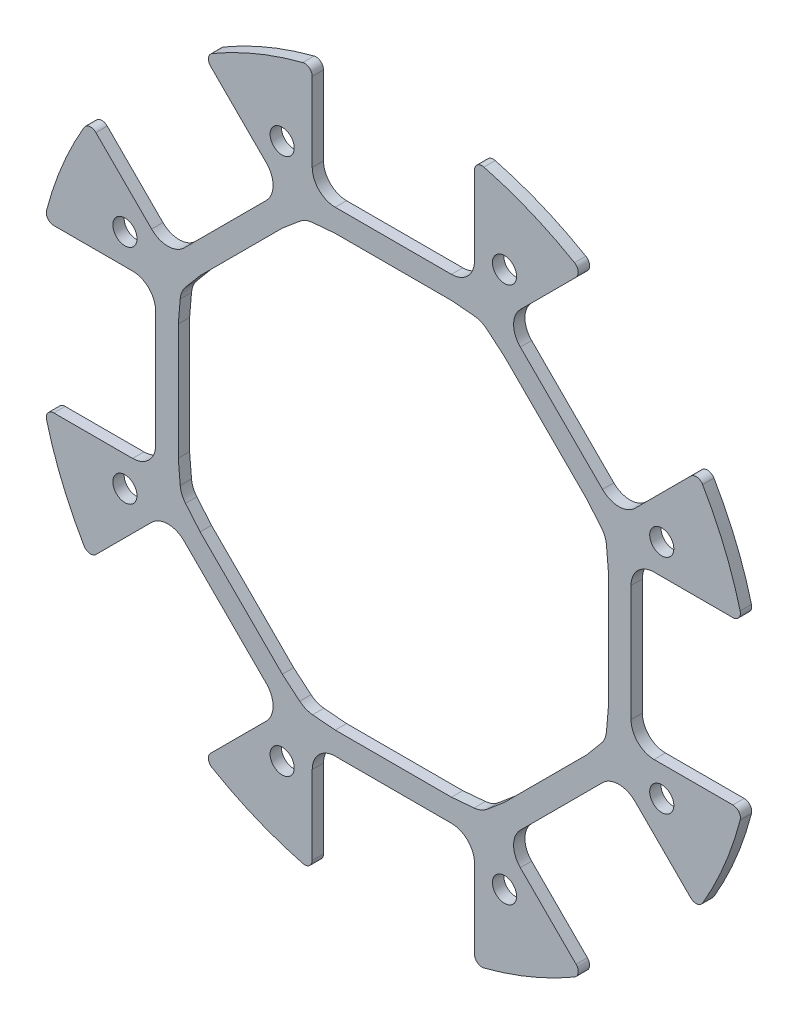
SolidWorks part; units mm, degrees
material "5052-H34"
ref_plane "正面" through (0, 0, 0) normal (0, 0, 1) x (1, 0, 0)
ref_plane "平面" through (0, 0, 0) normal (0, 1, 0) x (1, 0, 0)
ref_plane "右側面" through (0, 0, 0) normal (1, 0, 0) x (0, 0, -1)
sketch "ｽｹｯﾁ1" plane through (0, 0, 0) normal (0, 0, 1) x (1, 0, 0)
  circle A0 centre (0, 0) radius 47.5
  dimension "D1" = 95
extrude "ﾎﾞｽ - 押し出し1" add sketch "ｽｹｯﾁ1" along normal blind 1.5
sketch "ｽｹｯﾁ2" plane through (0, 0, 1.5) normal (0, 0, 1) x (1, 0, 0)
  line L0 (0, 0) -> (0, 47.5) construction
  line L1 (-10.75, 43.525) -> (-10.75, 52.5)
  line L2 (-10.75, 31.5) -> (10.75, 31.5)
  line L3 (-10.75, 31.5) -> (-10.75, 40.475)
  line L4 (-10.75, 52.5) -> (10.75, 52.5)
  line L5 (10.75, 31.5) -> (10.75, 40.475)
  line L6 (-10.75, 31.5) -> (10.75, 52.5) construction
  line L7 (-10.75, 52.5) -> (10.75, 31.5) construction
  line L8 (-13, 43.525) -> (-10.75, 43.525)
  line L9 (-13, 43.525) -> (-13, 40.475)
  line L10 (-13, 40.475) -> (-10.75, 40.475)
  line L11 (13, 43.525) -> (13, 40.475)
  line L12 (-13, 43.525) -> (13, 40.475) construction
  line L13 (-13, 40.475) -> (13, 43.525) construction
  line L14 (10.75, 43.525) -> (10.75, 52.5)
  line L15 (10.75, 43.525) -> (13, 43.525)
  line L17 (10.75, 40.475) -> (13, 40.475)
  circle A0 centre (0, 0) radius 47.5 construction
  point P5 (0, 42)
  point P10 (0, 42)
  dimension "D1" = 42
  dimension "D2" = 21.5
  dimension "D3" = 21
  dimension "D4" = 3.05
  dimension "D5" = 26
extrude "ｶｯﾄ - 押し出し1" cut sketch "ｽｹｯﾁ2" against normal through all
sketch "ｽｹｯﾁ3" plane through (0, 0, 1.5) normal (0, 0, 1) x (1, 0, 0)
  line L1 (-8.8388, -8.8388) -> (8.8388, -8.8388) construction
  line L2 (-8.8388, -8.8388) -> (-8.8388, 8.8388) construction
  line L3 (-8.8388, 8.8388) -> (8.8388, 8.8388) construction
  line L4 (8.8388, -8.8388) -> (8.8388, 8.8388) construction
  line L5 (-8.8388, -8.8388) -> (8.8388, 8.8388) construction
  line L6 (-8.8388, 8.8388) -> (8.8388, -8.8388) construction
  circle A0 centre (0, 0) radius 3.1
  circle A1 centre (0, 0) radius 6.5 construction
  circle A2 centre (0, 6.5) radius 1.6
  circle A3 centre (6.5, 0) radius 1.6
  circle A4 centre (0, -6.5) radius 1.6
  circle A5 centre (-6.5, 0) radius 1.6
  circle A6 centre (0, 0) radius 12.5 construction
  circle A7 centre (8.8388, 8.8388) radius 1.6
  circle A8 centre (8.8388, -8.8388) radius 1.6
  circle A9 centre (-8.8388, -8.8388) radius 1.6
  circle A10 centre (-8.8388, 8.8388) radius 1.6
  dimension "D1" = 6.2
  dimension "D2" = 13
  dimension "D3" = 3.2
  dimension "D5" = 25
  dimension "D6" = 3.2
  dimension "D4" = 4
  dimension "D7" = 4
extrude "ｶｯﾄ - 押し出し2" cut sketch "ｽｹｯﾁ3" against normal through all and the other way through all
sketch "ｽｹｯﾁ4" plane through (0, 0, 1.5) normal (0, 0, 1) x (1, 0, 0)
  line L0 (0, 31.5) -> (0, 0) construction
  line L1 (-10.75, 31.5) -> (10.75, 31.5) construction
  line L2 (0, 0) -> (14.7333, 35.5694) construction
  circle A0 centre (0, 0) radius 22.5 construction
  circle A1 centre (0, 0) radius 38.5 construction
  circle A2 centre (14.7333, 35.5694) radius 1.6
  circle A3 centre (8.6104, 20.7873) radius 1.6
  dimension "D1" = 45
  dimension "D2" = 77
  dimension "D4" = 3.2
  dimension "D3" = 22.5
extrude "ｶｯﾄ - 押し出し3" cut sketch "ｽｹｯﾁ4" against normal through all
sketch "ｽｹｯﾁ5" plane through (0, 0, 1.5) normal (0, 0, 1) x (1, 0, 0)
  line L0 (0, 0) -> (14.7333, 35.5694) construction
  line L1 (-10.75, 31.5) -> (10.75, 31.5) construction
  line L2 (-10.75, 31.5) -> (10.75, 31.5) construction
  line L3 (-7.1883, 26.5) -> (7.1883, 26.5)
  line L4 (-3.3281, 17.1806) -> (-7.1883, 26.5)
  line L5 (0, 31.5) -> (0, 0) construction
  line L6 (-10.75, 26.5) -> (10.75, 26.5) construction
  line L9 (-3.3281, 17.1806) -> (3.3281, 17.1806)
  line L10 (3.3281, 17.1806) -> (7.1883, 26.5)
  circle A0 centre (0, 0) radius 17.5 construction
  dimension "D3" = 35
  dimension "D2" = 7
  dimension "D1" = 5
extrude "ｶｯﾄ - 押し出し4" cut sketch "ｽｹｯﾁ5" against normal through all and the other way through all
fillet "ﾌｨﾚｯﾄ1" radius 1 6 edges at (-3.3281, 17.1806, 0.75) (3.3281, 17.1806, 0.75) (7.1883, 26.5, 0.75) (-7.1883, 26.5, 0.75) (10.75, 46.2676, 0.75) (-10.75, 46.2676, 0.75)
fillet "ﾌｨﾚｯﾄ2" radius 0.2 4 edges at (13, 43.525, 0.75) (13, 40.475, 0.75) (-13, 43.525, 0.75) (-13, 40.475, 0.75)
fillet "ﾌｨﾚｯﾄ3" radius 3.05 2 edges at (10.75, 31.5, 0.75) (-10.75, 31.5, 0.75)
ref_axis "軸1" through (0, 0, 0) along (0, 0, 1)
pattern_circular "円形ﾊﾟﾀｰﾝ1" count 8 over 360 about axis through (0, 0, 0) along (0, 0, 1) of "ｶｯﾄ - 押し出し1", "ﾌｨﾚｯﾄ1", "ｶｯﾄ - 押し出し4", "ｶｯﾄ - 押し出し3", "ﾌｨﾚｯﾄ2", "ﾌｨﾚｯﾄ3"
sketch "ｽｹｯﾁ6" plane through (0, 0, 1.5) normal (0, 0, 1) x (1, 0, 0)
  line L0 (7.7, 28.5) -> (-7.7, 28.5)
  line L1 (7.7, 28.5) -> (16.8291, 27.7186)
  line L2 (-7.7, 28.5) -> (-16.8291, 27.7186)
  line L3 (14.7078, 25.5973) -> (7.7, 31.5)
  line L4 (25.5973, 14.7078) -> (14.7078, 25.5973)
  line L5 (25.5973, 14.7078) -> (31.5, 7.7)
  line L6 (28.5, 7.7) -> (27.7186, 16.8291)
  line L7 (28.5, -7.7) -> (28.5, 7.7)
  line L8 (28.5, -7.7) -> (27.7186, -16.8291)
  line L9 (25.5973, -14.7078) -> (31.5, -7.7)
  line L10 (14.7078, -25.5973) -> (25.5973, -14.7078)
  line L11 (14.7078, -25.5973) -> (7.7, -31.5)
  line L12 (7.7, -28.5) -> (16.8291, -27.7186)
  line L13 (-7.7, -28.5) -> (7.7, -28.5)
  line L14 (-7.7, -28.5) -> (-16.8291, -27.7186)
  line L15 (-14.7078, -25.5973) -> (-7.7, -31.5)
  line L16 (-25.5973, -14.7078) -> (-14.7078, -25.5973)
  line L17 (-25.5973, -14.7078) -> (-31.5, -7.7)
  line L18 (-28.5, -7.7) -> (-27.7186, -16.8291)
  line L19 (-28.5, 7.7) -> (-28.5, -7.7)
  line L20 (-28.5, 7.7) -> (-27.7186, 16.8291)
  line L21 (-25.5973, 14.7078) -> (-31.5, 7.7)
  line L22 (-14.7078, 25.5973) -> (-25.5973, 14.7078)
  line L23 (-14.7078, 25.5973) -> (-7.7, 31.5)
  line L88 (39.4148, 24.212) -> (38.3782, 23.1754)
  line L89 (38.3782, 23.1754) -> (39.8278, 21.7259)
  line L90 (39.8278, 21.443) -> (37.954, 19.5692)
  line L91 (37.6711, 19.5692) -> (36.2215, 21.0187)
  line L92 (36.2215, 21.0187) -> (32.0319, 16.8291)
  line L93 (27.7186, 16.8291) -> (16.8291, 27.7186)
  line L94 (16.8291, 32.0319) -> (21.0187, 36.2215)
  line L95 (21.0187, 36.2215) -> (19.5692, 37.6711)
  line L96 (19.5692, 37.954) -> (21.443, 39.8278)
  line L97 (21.7259, 39.8278) -> (23.1754, 38.3782)
  line L98 (23.1754, 38.3782) -> (24.212, 39.4148)
  line L99 (10.75, 44.991) -> (10.75, 43.525)
  line L100 (10.75, 43.525) -> (12.8, 43.525)
  line L101 (13, 43.325) -> (13, 40.675)
  line L102 (12.8, 40.475) -> (10.75, 40.475)
  line L103 (10.75, 40.475) -> (10.75, 34.55)
  line L104 (7.7, 31.5) -> (-7.7, 31.5)
  line L105 (-10.75, 34.55) -> (-10.75, 40.475)
  line L106 (-10.75, 40.475) -> (-12.8, 40.475)
  line L107 (-13, 40.675) -> (-13, 43.325)
  line L108 (-12.8, 43.525) -> (-10.75, 43.525)
  line L109 (-10.75, 43.525) -> (-10.75, 44.991)
  line L110 (-24.212, 39.4148) -> (-23.1754, 38.3782)
  line L111 (-23.1754, 38.3782) -> (-21.7259, 39.8278)
  line L112 (-21.443, 39.8278) -> (-19.5692, 37.954)
  line L113 (-19.5692, 37.6711) -> (-21.0187, 36.2215)
  line L114 (-21.0187, 36.2215) -> (-16.8291, 32.0319)
  line L115 (-16.8291, 27.7186) -> (-27.7186, 16.8291)
  line L116 (-32.0319, 16.8291) -> (-36.2215, 21.0187)
  line L117 (-36.2215, 21.0187) -> (-37.6711, 19.5692)
  line L118 (-37.954, 19.5692) -> (-39.8278, 21.443)
  line L119 (-39.8278, 21.7259) -> (-38.3782, 23.1754)
  line L120 (-38.3782, 23.1754) -> (-39.4148, 24.212)
  line L121 (-44.991, 10.75) -> (-43.525, 10.75)
  line L122 (-43.525, 10.75) -> (-43.525, 12.8)
  line L123 (-43.325, 13) -> (-40.675, 13)
  line L124 (-40.475, 12.8) -> (-40.475, 10.75)
  line L125 (-40.475, 10.75) -> (-34.55, 10.75)
  line L126 (-31.5, 7.7) -> (-31.5, -7.7)
  line L127 (-34.55, -10.75) -> (-40.475, -10.75)
  line L128 (-40.475, -10.75) -> (-40.475, -12.8)
  line L129 (-40.675, -13) -> (-43.325, -13)
  line L130 (-43.525, -12.8) -> (-43.525, -10.75)
  line L131 (-43.525, -10.75) -> (-44.991, -10.75)
  line L132 (-39.4148, -24.212) -> (-38.3782, -23.1754)
  line L133 (-38.3782, -23.1754) -> (-39.8278, -21.7259)
  line L134 (-39.8278, -21.443) -> (-37.954, -19.5692)
  line L135 (-37.6711, -19.5692) -> (-36.2215, -21.0187)
  line L136 (-36.2215, -21.0187) -> (-32.0319, -16.8291)
  line L137 (-27.7186, -16.8291) -> (-16.8291, -27.7186)
  line L138 (-16.8291, -32.0319) -> (-21.0187, -36.2215)
  line L139 (-21.0187, -36.2215) -> (-19.5692, -37.6711)
  line L140 (-19.5692, -37.954) -> (-21.443, -39.8278)
  line L141 (-21.7259, -39.8278) -> (-23.1754, -38.3782)
  line L142 (-23.1754, -38.3782) -> (-24.212, -39.4148)
  line L143 (-10.75, -44.991) -> (-10.75, -43.525)
  line L144 (-10.75, -43.525) -> (-12.8, -43.525)
  line L145 (-13, -43.325) -> (-13, -40.675)
  line L146 (-12.8, -40.475) -> (-10.75, -40.475)
  line L147 (-10.75, -40.475) -> (-10.75, -34.55)
  line L148 (-7.7, -31.5) -> (7.7, -31.5)
  line L149 (10.75, -34.55) -> (10.75, -40.475)
  line L150 (10.75, -40.475) -> (12.8, -40.475)
  line L151 (13, -40.675) -> (13, -43.325)
  line L152 (12.8, -43.525) -> (10.75, -43.525)
  line L153 (10.75, -43.525) -> (10.75, -44.991)
  line L154 (24.212, -39.4148) -> (23.1754, -38.3782)
  line L155 (23.1754, -38.3782) -> (21.7259, -39.8278)
  line L156 (21.443, -39.8278) -> (19.5692, -37.954)
  line L157 (19.5692, -37.6711) -> (21.0187, -36.2215)
  line L158 (21.0187, -36.2215) -> (16.8291, -32.0319)
  line L159 (16.8291, -27.7186) -> (27.7186, -16.8291)
  line L160 (32.0319, -16.8291) -> (36.2215, -21.0187)
  line L161 (36.2215, -21.0187) -> (37.6711, -19.5692)
  line L162 (37.954, -19.5692) -> (39.8278, -21.443)
  line L163 (39.8278, -21.7259) -> (38.3782, -23.1754)
  line L164 (38.3782, -23.1754) -> (39.4148, -24.212)
  line L165 (44.991, -10.75) -> (43.525, -10.75)
  line L166 (43.525, -10.75) -> (43.525, -12.8)
  line L167 (43.325, -13) -> (40.675, -13)
  line L168 (40.475, -12.8) -> (40.475, -10.75)
  line L169 (40.475, -10.75) -> (34.55, -10.75)
  line L170 (31.5, -7.7) -> (31.5, 7.7)
  line L171 (34.55, 10.75) -> (40.475, 10.75)
  line L172 (40.475, 10.75) -> (40.475, 12.8)
  line L173 (40.675, 13) -> (43.325, 13)
  line L174 (43.525, 12.8) -> (43.525, 10.75)
  line L175 (43.525, 10.75) -> (44.991, 10.75)
  line L176 (39.4148, 24.212) -> (38.3782, 23.1754)
  line L177 (38.3782, 23.1754) -> (39.8278, 21.7259)
  line L178 (39.8278, 21.443) -> (37.954, 19.5692)
  line L179 (37.6711, 19.5692) -> (36.2215, 21.0187)
  line L180 (36.2215, 21.0187) -> (32.0319, 16.8291)
  line L181 (27.7186, 16.8291) -> (16.8291, 27.7186)
  line L182 (16.8291, 32.0319) -> (21.0187, 36.2215)
  line L183 (21.0187, 36.2215) -> (19.5692, 37.6711)
  line L184 (19.5692, 37.954) -> (21.443, 39.8278)
  line L185 (21.7259, 39.8278) -> (23.1754, 38.3782)
  line L186 (23.1754, 38.3782) -> (24.212, 39.4148)
  line L187 (10.75, 44.991) -> (10.75, 43.525)
  line L188 (10.75, 43.525) -> (12.8, 43.525)
  line L189 (13, 43.325) -> (13, 40.675)
  line L190 (12.8, 40.475) -> (10.75, 40.475)
  line L191 (10.75, 40.475) -> (10.75, 34.55)
  line L192 (7.7, 31.5) -> (-7.7, 31.5)
  line L193 (-10.75, 34.55) -> (-10.75, 40.475)
  line L194 (-10.75, 40.475) -> (-12.8, 40.475)
  line L195 (-13, 40.675) -> (-13, 43.325)
  line L196 (-12.8, 43.525) -> (-10.75, 43.525)
  line L197 (-10.75, 43.525) -> (-10.75, 44.991)
  line L198 (-24.212, 39.4148) -> (-23.1754, 38.3782)
  line L199 (-23.1754, 38.3782) -> (-21.7259, 39.8278)
  line L200 (-21.443, 39.8278) -> (-19.5692, 37.954)
  line L201 (-19.5692, 37.6711) -> (-21.0187, 36.2215)
  line L202 (-21.0187, 36.2215) -> (-16.8291, 32.0319)
  line L203 (-16.8291, 27.7186) -> (-27.7186, 16.8291)
  line L204 (-32.0319, 16.8291) -> (-36.2215, 21.0187)
  line L205 (-36.2215, 21.0187) -> (-37.6711, 19.5692)
  line L206 (-37.954, 19.5692) -> (-39.8278, 21.443)
  line L207 (-39.8278, 21.7259) -> (-38.3782, 23.1754)
  line L208 (-38.3782, 23.1754) -> (-39.4148, 24.212)
  line L209 (-44.991, 10.75) -> (-43.525, 10.75)
  line L210 (-43.525, 10.75) -> (-43.525, 12.8)
  line L211 (-43.325, 13) -> (-40.675, 13)
  line L212 (-40.475, 12.8) -> (-40.475, 10.75)
  line L213 (-40.475, 10.75) -> (-34.55, 10.75)
  line L214 (-31.5, 7.7) -> (-31.5, -7.7)
  line L215 (-34.55, -10.75) -> (-40.475, -10.75)
  line L216 (-40.475, -10.75) -> (-40.475, -12.8)
  line L217 (-40.675, -13) -> (-43.325, -13)
  line L218 (-43.525, -12.8) -> (-43.525, -10.75)
  line L219 (-43.525, -10.75) -> (-44.991, -10.75)
  line L220 (-39.4148, -24.212) -> (-38.3782, -23.1754)
  line L221 (-38.3782, -23.1754) -> (-39.8278, -21.7259)
  line L222 (-39.8278, -21.443) -> (-37.954, -19.5692)
  line L223 (-37.6711, -19.5692) -> (-36.2215, -21.0187)
  line L224 (-36.2215, -21.0187) -> (-32.0319, -16.8291)
  line L225 (-27.7186, -16.8291) -> (-16.8291, -27.7186)
  line L226 (-16.8291, -32.0319) -> (-21.0187, -36.2215)
  line L227 (-21.0187, -36.2215) -> (-19.5692, -37.6711)
  line L228 (-19.5692, -37.954) -> (-21.443, -39.8278)
  line L229 (-21.7259, -39.8278) -> (-23.1754, -38.3782)
  line L230 (-23.1754, -38.3782) -> (-24.212, -39.4148)
  line L231 (-10.75, -44.991) -> (-10.75, -43.525)
  line L232 (-10.75, -43.525) -> (-12.8, -43.525)
  line L233 (-13, -43.325) -> (-13, -40.675)
  line L234 (-12.8, -40.475) -> (-10.75, -40.475)
  line L235 (-10.75, -40.475) -> (-10.75, -34.55)
  line L236 (-7.7, -31.5) -> (7.7, -31.5)
  line L237 (10.75, -34.55) -> (10.75, -40.475)
  line L238 (10.75, -40.475) -> (12.8, -40.475)
  line L239 (13, -40.675) -> (13, -43.325)
  line L240 (12.8, -43.525) -> (10.75, -43.525)
  line L241 (10.75, -43.525) -> (10.75, -44.991)
  line L242 (24.212, -39.4148) -> (23.1754, -38.3782)
  line L243 (23.1754, -38.3782) -> (21.7259, -39.8278)
  line L244 (21.443, -39.8278) -> (19.5692, -37.954)
  line L245 (19.5692, -37.6711) -> (21.0187, -36.2215)
  line L246 (21.0187, -36.2215) -> (16.8291, -32.0319)
  line L247 (16.8291, -27.7186) -> (27.7186, -16.8291)
  line L248 (32.0319, -16.8291) -> (36.2215, -21.0187)
  line L249 (36.2215, -21.0187) -> (37.6711, -19.5692)
  line L250 (37.954, -19.5692) -> (39.8278, -21.443)
  line L251 (39.8278, -21.7259) -> (38.3782, -23.1754)
  line L252 (38.3782, -23.1754) -> (39.4148, -24.212)
  line L253 (44.991, -10.75) -> (43.525, -10.75)
  line L254 (43.525, -10.75) -> (43.525, -12.8)
  line L255 (43.325, -13) -> (40.675, -13)
  line L256 (40.475, -12.8) -> (40.475, -10.75)
  line L257 (40.475, -10.75) -> (34.55, -10.75)
  line L258 (31.5, -7.7) -> (31.5, 7.7)
  line L259 (34.55, 10.75) -> (40.475, 10.75)
  line L260 (40.475, 10.75) -> (40.475, 12.8)
  line L261 (40.675, 13) -> (43.325, 13)
  line L262 (43.525, 12.8) -> (43.525, 10.75)
  line L263 (43.525, 10.75) -> (44.991, 10.75)
  arc A72 (45.9585, 12.0027) -> (40.9848, 24.0104) centre (0, 0) ccw
  arc A73 (40.9848, 24.0104) -> (39.4148, 24.212) centre (40.1219, 23.5049) ccw
  arc A74 (39.8278, 21.443) -> (39.8278, 21.7259) centre (39.6864, 21.5844) ccw
  arc A75 (37.6711, 19.5692) -> (37.954, 19.5692) centre (37.8125, 19.7106) ccw
  arc A76 (27.7186, 16.8291) -> (32.0319, 16.8291) centre (29.8753, 18.9858) ccw
  arc A77 (16.8291, 32.0319) -> (16.8291, 27.7186) centre (18.9858, 29.8753) ccw
  arc A78 (19.5692, 37.954) -> (19.5692, 37.6711) centre (19.7106, 37.8125) ccw
  arc A79 (21.7259, 39.8278) -> (21.443, 39.8278) centre (21.5844, 39.6864) ccw
  arc A80 (24.212, 39.4148) -> (24.0104, 40.9848) centre (23.5049, 40.1219) ccw
  arc A81 (24.0104, 40.9848) -> (12.0027, 45.9585) centre (0, 0) ccw
  arc A82 (12.0027, 45.9585) -> (10.75, 44.991) centre (11.75, 44.991) ccw
  arc A83 (13, 43.325) -> (12.8, 43.525) centre (12.8, 43.325) ccw
  arc A84 (12.8, 40.475) -> (13, 40.675) centre (12.8, 40.675) ccw
  arc A85 (7.7, 31.5) -> (10.75, 34.55) centre (7.7, 34.55) ccw
  arc A86 (-10.75, 34.55) -> (-7.7, 31.5) centre (-7.7, 34.55) ccw
  arc A87 (-13, 40.675) -> (-12.8, 40.475) centre (-12.8, 40.675) ccw
  arc A88 (-12.8, 43.525) -> (-13, 43.325) centre (-12.8, 43.325) ccw
  arc A89 (-10.75, 44.991) -> (-12.0027, 45.9585) centre (-11.75, 44.991) ccw
  arc A90 (-12.0027, 45.9585) -> (-24.0104, 40.9848) centre (0, 0) ccw
  arc A91 (-24.0104, 40.9848) -> (-24.212, 39.4148) centre (-23.5049, 40.1219) ccw
  arc A92 (-21.443, 39.8278) -> (-21.7259, 39.8278) centre (-21.5844, 39.6864) ccw
  arc A93 (-19.5692, 37.6711) -> (-19.5692, 37.954) centre (-19.7106, 37.8125) ccw
  arc A94 (-16.8291, 27.7186) -> (-16.8291, 32.0319) centre (-18.9858, 29.8753) ccw
  arc A95 (-32.0319, 16.8291) -> (-27.7186, 16.8291) centre (-29.8753, 18.9858) ccw
  arc A96 (-37.954, 19.5692) -> (-37.6711, 19.5692) centre (-37.8125, 19.7106) ccw
  arc A97 (-39.8278, 21.7259) -> (-39.8278, 21.443) centre (-39.6864, 21.5844) ccw
  arc A98 (-39.4148, 24.212) -> (-40.9848, 24.0104) centre (-40.1219, 23.5049) ccw
  arc A99 (-40.9848, 24.0104) -> (-45.9585, 12.0027) centre (0, 0) ccw
  arc A100 (-45.9585, 12.0027) -> (-44.991, 10.75) centre (-44.991, 11.75) ccw
  arc A101 (-43.325, 13) -> (-43.525, 12.8) centre (-43.325, 12.8) ccw
  arc A102 (-40.475, 12.8) -> (-40.675, 13) centre (-40.675, 12.8) ccw
  arc A103 (-31.5, 7.7) -> (-34.55, 10.75) centre (-34.55, 7.7) ccw
  arc A104 (-34.55, -10.75) -> (-31.5, -7.7) centre (-34.55, -7.7) ccw
  arc A105 (-40.675, -13) -> (-40.475, -12.8) centre (-40.675, -12.8) ccw
  arc A106 (-43.525, -12.8) -> (-43.325, -13) centre (-43.325, -12.8) ccw
  arc A107 (-44.991, -10.75) -> (-45.9585, -12.0027) centre (-44.991, -11.75) ccw
  arc A108 (-45.9585, -12.0027) -> (-40.9848, -24.0104) centre (0, 0) ccw
  arc A109 (-40.9848, -24.0104) -> (-39.4148, -24.212) centre (-40.1219, -23.5049) ccw
  arc A110 (-39.8278, -21.443) -> (-39.8278, -21.7259) centre (-39.6864, -21.5844) ccw
  arc A111 (-37.6711, -19.5692) -> (-37.954, -19.5692) centre (-37.8125, -19.7106) ccw
  arc A112 (-27.7186, -16.8291) -> (-32.0319, -16.8291) centre (-29.8753, -18.9858) ccw
  arc A113 (-16.8291, -32.0319) -> (-16.8291, -27.7186) centre (-18.9858, -29.8753) ccw
  arc A114 (-19.5692, -37.954) -> (-19.5692, -37.6711) centre (-19.7106, -37.8125) ccw
  arc A115 (-21.7259, -39.8278) -> (-21.443, -39.8278) centre (-21.5844, -39.6864) ccw
  arc A116 (-24.212, -39.4148) -> (-24.0104, -40.9848) centre (-23.5049, -40.1219) ccw
  arc A117 (-24.0104, -40.9848) -> (-12.0027, -45.9585) centre (0, 0) ccw
  arc A118 (-12.0027, -45.9585) -> (-10.75, -44.991) centre (-11.75, -44.991) ccw
  arc A119 (-13, -43.325) -> (-12.8, -43.525) centre (-12.8, -43.325) ccw
  arc A120 (-12.8, -40.475) -> (-13, -40.675) centre (-12.8, -40.675) ccw
  arc A121 (-7.7, -31.5) -> (-10.75, -34.55) centre (-7.7, -34.55) ccw
  arc A122 (10.75, -34.55) -> (7.7, -31.5) centre (7.7, -34.55) ccw
  arc A123 (13, -40.675) -> (12.8, -40.475) centre (12.8, -40.675) ccw
  arc A124 (12.8, -43.525) -> (13, -43.325) centre (12.8, -43.325) ccw
  arc A125 (10.75, -44.991) -> (12.0027, -45.9585) centre (11.75, -44.991) ccw
  arc A126 (12.0027, -45.9585) -> (24.0104, -40.9848) centre (0, 0) ccw
  arc A127 (24.0104, -40.9848) -> (24.212, -39.4148) centre (23.5049, -40.1219) ccw
  arc A128 (21.443, -39.8278) -> (21.7259, -39.8278) centre (21.5844, -39.6864) ccw
  arc A129 (19.5692, -37.6711) -> (19.5692, -37.954) centre (19.7106, -37.8125) ccw
  arc A130 (16.8291, -27.7186) -> (16.8291, -32.0319) centre (18.9858, -29.8753) ccw
  arc A131 (32.0319, -16.8291) -> (27.7186, -16.8291) centre (29.8753, -18.9858) ccw
  arc A132 (37.954, -19.5692) -> (37.6711, -19.5692) centre (37.8125, -19.7106) ccw
  arc A133 (39.8278, -21.7259) -> (39.8278, -21.443) centre (39.6864, -21.5844) ccw
  arc A134 (39.4148, -24.212) -> (40.9848, -24.0104) centre (40.1219, -23.5049) ccw
  arc A135 (40.9848, -24.0104) -> (45.9585, -12.0027) centre (0, 0) ccw
  arc A136 (45.9585, -12.0027) -> (44.991, -10.75) centre (44.991, -11.75) ccw
  arc A137 (43.325, -13) -> (43.525, -12.8) centre (43.325, -12.8) ccw
  arc A138 (40.475, -12.8) -> (40.675, -13) centre (40.675, -12.8) ccw
  arc A139 (31.5, -7.7) -> (34.55, -10.75) centre (34.55, -7.7) ccw
  arc A140 (34.55, 10.75) -> (31.5, 7.7) centre (34.55, 7.7) ccw
  arc A141 (40.675, 13) -> (40.475, 12.8) centre (40.675, 12.8) ccw
  arc A142 (43.525, 12.8) -> (43.325, 13) centre (43.325, 12.8) ccw
  arc A143 (44.991, 10.75) -> (45.9585, 12.0027) centre (44.991, 11.75) ccw
  arc A144 (45.9585, 12.0027) -> (40.9848, 24.0104) centre (0, 0) ccw
  arc A145 (40.9848, 24.0104) -> (39.4148, 24.212) centre (40.1219, 23.5049) ccw
  arc A146 (39.8278, 21.443) -> (39.8278, 21.7259) centre (39.6864, 21.5844) ccw
  arc A147 (37.6711, 19.5692) -> (37.954, 19.5692) centre (37.8125, 19.7106) ccw
  arc A148 (27.7186, 16.8291) -> (32.0319, 16.8291) centre (29.8753, 18.9858) ccw
  arc A149 (16.8291, 32.0319) -> (16.8291, 27.7186) centre (18.9858, 29.8753) ccw
  arc A150 (19.5692, 37.954) -> (19.5692, 37.6711) centre (19.7106, 37.8125) ccw
  arc A151 (21.7259, 39.8278) -> (21.443, 39.8278) centre (21.5844, 39.6864) ccw
  arc A152 (24.212, 39.4148) -> (24.0104, 40.9848) centre (23.5049, 40.1219) ccw
  arc A153 (24.0104, 40.9848) -> (12.0027, 45.9585) centre (0, 0) ccw
  arc A154 (12.0027, 45.9585) -> (10.75, 44.991) centre (11.75, 44.991) ccw
  arc A155 (13, 43.325) -> (12.8, 43.525) centre (12.8, 43.325) ccw
  arc A156 (12.8, 40.475) -> (13, 40.675) centre (12.8, 40.675) ccw
  arc A157 (7.7, 31.5) -> (10.75, 34.55) centre (7.7, 34.55) ccw
  arc A158 (-10.75, 34.55) -> (-7.7, 31.5) centre (-7.7, 34.55) ccw
  arc A159 (-13, 40.675) -> (-12.8, 40.475) centre (-12.8, 40.675) ccw
  arc A160 (-12.8, 43.525) -> (-13, 43.325) centre (-12.8, 43.325) ccw
  arc A161 (-10.75, 44.991) -> (-12.0027, 45.9585) centre (-11.75, 44.991) ccw
  arc A162 (-12.0027, 45.9585) -> (-24.0104, 40.9848) centre (0, 0) ccw
  arc A163 (-24.0104, 40.9848) -> (-24.212, 39.4148) centre (-23.5049, 40.1219) ccw
  arc A164 (-21.443, 39.8278) -> (-21.7259, 39.8278) centre (-21.5844, 39.6864) ccw
  arc A165 (-19.5692, 37.6711) -> (-19.5692, 37.954) centre (-19.7106, 37.8125) ccw
  arc A166 (-16.8291, 27.7186) -> (-16.8291, 32.0319) centre (-18.9858, 29.8753) ccw
  arc A167 (-32.0319, 16.8291) -> (-27.7186, 16.8291) centre (-29.8753, 18.9858) ccw
  arc A168 (-37.954, 19.5692) -> (-37.6711, 19.5692) centre (-37.8125, 19.7106) ccw
  arc A169 (-39.8278, 21.7259) -> (-39.8278, 21.443) centre (-39.6864, 21.5844) ccw
  arc A170 (-39.4148, 24.212) -> (-40.9848, 24.0104) centre (-40.1219, 23.5049) ccw
  arc A171 (-40.9848, 24.0104) -> (-45.9585, 12.0027) centre (0, 0) ccw
  arc A172 (-45.9585, 12.0027) -> (-44.991, 10.75) centre (-44.991, 11.75) ccw
  arc A173 (-43.325, 13) -> (-43.525, 12.8) centre (-43.325, 12.8) ccw
  arc A174 (-40.475, 12.8) -> (-40.675, 13) centre (-40.675, 12.8) ccw
  arc A175 (-31.5, 7.7) -> (-34.55, 10.75) centre (-34.55, 7.7) ccw
  arc A176 (-34.55, -10.75) -> (-31.5, -7.7) centre (-34.55, -7.7) ccw
  arc A177 (-40.675, -13) -> (-40.475, -12.8) centre (-40.675, -12.8) ccw
  arc A178 (-43.525, -12.8) -> (-43.325, -13) centre (-43.325, -12.8) ccw
  arc A179 (-44.991, -10.75) -> (-45.9585, -12.0027) centre (-44.991, -11.75) ccw
  arc A180 (-45.9585, -12.0027) -> (-40.9848, -24.0104) centre (0, 0) ccw
  arc A181 (-40.9848, -24.0104) -> (-39.4148, -24.212) centre (-40.1219, -23.5049) ccw
  arc A182 (-39.8278, -21.443) -> (-39.8278, -21.7259) centre (-39.6864, -21.5844) ccw
  arc A183 (-37.6711, -19.5692) -> (-37.954, -19.5692) centre (-37.8125, -19.7106) ccw
  arc A184 (-27.7186, -16.8291) -> (-32.0319, -16.8291) centre (-29.8753, -18.9858) ccw
  arc A185 (-16.8291, -32.0319) -> (-16.8291, -27.7186) centre (-18.9858, -29.8753) ccw
  arc A186 (-19.5692, -37.954) -> (-19.5692, -37.6711) centre (-19.7106, -37.8125) ccw
  arc A187 (-21.7259, -39.8278) -> (-21.443, -39.8278) centre (-21.5844, -39.6864) ccw
  arc A188 (-24.212, -39.4148) -> (-24.0104, -40.9848) centre (-23.5049, -40.1219) ccw
  arc A189 (-24.0104, -40.9848) -> (-12.0027, -45.9585) centre (0, 0) ccw
  arc A190 (-12.0027, -45.9585) -> (-10.75, -44.991) centre (-11.75, -44.991) ccw
  arc A191 (-13, -43.325) -> (-12.8, -43.525) centre (-12.8, -43.325) ccw
  arc A192 (-12.8, -40.475) -> (-13, -40.675) centre (-12.8, -40.675) ccw
  arc A193 (-7.7, -31.5) -> (-10.75, -34.55) centre (-7.7, -34.55) ccw
  arc A194 (10.75, -34.55) -> (7.7, -31.5) centre (7.7, -34.55) ccw
  arc A195 (13, -40.675) -> (12.8, -40.475) centre (12.8, -40.675) ccw
  arc A196 (12.8, -43.525) -> (13, -43.325) centre (12.8, -43.325) ccw
  arc A197 (10.75, -44.991) -> (12.0027, -45.9585) centre (11.75, -44.991) ccw
  arc A198 (12.0027, -45.9585) -> (24.0104, -40.9848) centre (0, 0) ccw
  arc A199 (24.0104, -40.9848) -> (24.212, -39.4148) centre (23.5049, -40.1219) ccw
  arc A200 (21.443, -39.8278) -> (21.7259, -39.8278) centre (21.5844, -39.6864) ccw
  arc A201 (19.5692, -37.6711) -> (19.5692, -37.954) centre (19.7106, -37.8125) ccw
  arc A202 (16.8291, -27.7186) -> (16.8291, -32.0319) centre (18.9858, -29.8753) ccw
  arc A203 (32.0319, -16.8291) -> (27.7186, -16.8291) centre (29.8753, -18.9858) ccw
  arc A204 (37.954, -19.5692) -> (37.6711, -19.5692) centre (37.8125, -19.7106) ccw
  arc A205 (39.8278, -21.7259) -> (39.8278, -21.443) centre (39.6864, -21.5844) ccw
  arc A206 (39.4148, -24.212) -> (40.9848, -24.0104) centre (40.1219, -23.5049) ccw
  arc A207 (40.9848, -24.0104) -> (45.9585, -12.0027) centre (0, 0) ccw
  arc A208 (45.9585, -12.0027) -> (44.991, -10.75) centre (44.991, -11.75) ccw
  arc A209 (43.325, -13) -> (43.525, -12.8) centre (43.325, -12.8) ccw
  arc A210 (40.475, -12.8) -> (40.675, -13) centre (40.675, -12.8) ccw
  arc A211 (31.5, -7.7) -> (34.55, -10.75) centre (34.55, -7.7) ccw
  arc A212 (34.55, 10.75) -> (31.5, 7.7) centre (34.55, 7.7) ccw
  arc A213 (40.675, 13) -> (40.475, 12.8) centre (40.675, 12.8) ccw
  arc A214 (43.525, 12.8) -> (43.325, 13) centre (43.325, 12.8) ccw
  arc A215 (44.991, 10.75) -> (45.9585, 12.0027) centre (44.991, 11.75) ccw
  dimension "D4" = 3
  dimension "D5" = 3
  dimension "D1" = 0
  dimension "D2" = 3
  dimension "D3" = 8
extrude "ｶｯﾄ - 押し出し5" cut sketch "ｽｹｯﾁ6" against normal through all contours L23 L22 L21 L20 L19 L18 L17 L16 L15 L14 L13 L12 L11 L10 L9 L8 L7 L6 L5 L4 L3 L1 L0 L2
sketch "ｽｹｯﾁ7" plane through (0, 0, 1.5) normal (0, 0, 1) x (1, 0, 0)
  line L0 (-10.75, 43.525) -> (-10.75, 40.475)
  line L1 (10.75, 43.525) -> (10.75, 40.475)
  line L2 (23.1754, 38.3782) -> (21.0187, 36.2215)
  line L3 (38.3782, 23.1754) -> (36.2215, 21.0187)
  line L4 (43.525, 10.75) -> (40.475, 10.75)
  line L5 (43.525, -10.75) -> (40.475, -10.75)
  line L6 (38.3782, -23.1754) -> (36.2215, -21.0187)
  line L7 (23.1754, -38.3782) -> (21.0187, -36.2215)
  line L8 (10.75, -43.525) -> (10.75, -40.475)
  line L9 (-10.75, -43.525) -> (-10.75, -40.475)
  line L10 (-23.1754, -38.3782) -> (-21.0187, -36.2215)
  line L11 (-38.3782, -23.1754) -> (-36.2215, -21.0187)
  line L12 (-43.525, -10.75) -> (-40.475, -10.75)
  line L13 (-43.525, 10.75) -> (-40.475, 10.75)
  line L14 (-38.3782, 23.1754) -> (-36.2215, 21.0187)
  line L15 (-23.1754, 38.3782) -> (-21.0187, 36.2215)
  line L88 (39.4148, 24.212) -> (38.3782, 23.1754)
  line L89 (38.3782, 23.1754) -> (39.8278, 21.7259)
  line L90 (39.8278, 21.443) -> (37.954, 19.5692)
  line L91 (37.6711, 19.5692) -> (36.2215, 21.0187)
  line L92 (36.2215, 21.0187) -> (32.0319, 16.8291)
  line L93 (27.7186, 16.8291) -> (16.8291, 27.7186)
  line L94 (16.8291, 32.0319) -> (21.0187, 36.2215)
  line L95 (21.0187, 36.2215) -> (19.5692, 37.6711)
  line L96 (19.5692, 37.954) -> (21.443, 39.8278)
  line L97 (21.7259, 39.8278) -> (23.1754, 38.3782)
  line L98 (23.1754, 38.3782) -> (24.212, 39.4148)
  line L99 (10.75, 44.991) -> (10.75, 43.525)
  line L100 (10.75, 43.525) -> (12.8, 43.525)
  line L101 (13, 43.325) -> (13, 40.675)
  line L102 (12.8, 40.475) -> (10.75, 40.475)
  line L103 (10.75, 40.475) -> (10.75, 34.55)
  line L104 (7.7, 31.5) -> (-7.7, 31.5)
  line L105 (-10.75, 34.55) -> (-10.75, 40.475)
  line L106 (-10.75, 40.475) -> (-12.8, 40.475)
  line L107 (-13, 40.675) -> (-13, 43.325)
  line L108 (-12.8, 43.525) -> (-10.75, 43.525)
  line L109 (-10.75, 43.525) -> (-10.75, 44.991)
  line L110 (-24.212, 39.4148) -> (-23.1754, 38.3782)
  line L111 (-23.1754, 38.3782) -> (-21.7259, 39.8278)
  line L112 (-21.443, 39.8278) -> (-19.5692, 37.954)
  line L113 (-19.5692, 37.6711) -> (-21.0187, 36.2215)
  line L114 (-21.0187, 36.2215) -> (-16.8291, 32.0319)
  line L115 (-16.8291, 27.7186) -> (-27.7186, 16.8291)
  line L116 (-32.0319, 16.8291) -> (-36.2215, 21.0187)
  line L117 (-36.2215, 21.0187) -> (-37.6711, 19.5692)
  line L118 (-37.954, 19.5692) -> (-39.8278, 21.443)
  line L119 (-39.8278, 21.7259) -> (-38.3782, 23.1754)
  line L120 (-38.3782, 23.1754) -> (-39.4148, 24.212)
  line L121 (-44.991, 10.75) -> (-43.525, 10.75)
  line L122 (-43.525, 10.75) -> (-43.525, 12.8)
  line L123 (-43.325, 13) -> (-40.675, 13)
  line L124 (-40.475, 12.8) -> (-40.475, 10.75)
  line L125 (-40.475, 10.75) -> (-34.55, 10.75)
  line L126 (-31.5, 7.7) -> (-31.5, -7.7)
  line L127 (-34.55, -10.75) -> (-40.475, -10.75)
  line L128 (-40.475, -10.75) -> (-40.475, -12.8)
  line L129 (-40.675, -13) -> (-43.325, -13)
  line L130 (-43.525, -12.8) -> (-43.525, -10.75)
  line L131 (-43.525, -10.75) -> (-44.991, -10.75)
  line L132 (-39.4148, -24.212) -> (-38.3782, -23.1754)
  line L133 (-38.3782, -23.1754) -> (-39.8278, -21.7259)
  line L134 (-39.8278, -21.443) -> (-37.954, -19.5692)
  line L135 (-37.6711, -19.5692) -> (-36.2215, -21.0187)
  line L136 (-36.2215, -21.0187) -> (-32.0319, -16.8291)
  line L137 (-27.7186, -16.8291) -> (-16.8291, -27.7186)
  line L138 (-16.8291, -32.0319) -> (-21.0187, -36.2215)
  line L139 (-21.0187, -36.2215) -> (-19.5692, -37.6711)
  line L140 (-19.5692, -37.954) -> (-21.443, -39.8278)
  line L141 (-21.7259, -39.8278) -> (-23.1754, -38.3782)
  line L142 (-23.1754, -38.3782) -> (-24.212, -39.4148)
  line L143 (-10.75, -44.991) -> (-10.75, -43.525)
  line L144 (-10.75, -43.525) -> (-12.8, -43.525)
  line L145 (-13, -43.325) -> (-13, -40.675)
  line L146 (-12.8, -40.475) -> (-10.75, -40.475)
  line L147 (-10.75, -40.475) -> (-10.75, -34.55)
  line L148 (-7.7, -31.5) -> (7.7, -31.5)
  line L149 (10.75, -34.55) -> (10.75, -40.475)
  line L150 (10.75, -40.475) -> (12.8, -40.475)
  line L151 (13, -40.675) -> (13, -43.325)
  line L152 (12.8, -43.525) -> (10.75, -43.525)
  line L153 (10.75, -43.525) -> (10.75, -44.991)
  line L154 (24.212, -39.4148) -> (23.1754, -38.3782)
  line L155 (23.1754, -38.3782) -> (21.7259, -39.8278)
  line L156 (21.443, -39.8278) -> (19.5692, -37.954)
  line L157 (19.5692, -37.6711) -> (21.0187, -36.2215)
  line L158 (21.0187, -36.2215) -> (16.8291, -32.0319)
  line L159 (16.8291, -27.7186) -> (27.7186, -16.8291)
  line L160 (32.0319, -16.8291) -> (36.2215, -21.0187)
  line L161 (36.2215, -21.0187) -> (37.6711, -19.5692)
  line L162 (37.954, -19.5692) -> (39.8278, -21.443)
  line L163 (39.8278, -21.7259) -> (38.3782, -23.1754)
  line L164 (38.3782, -23.1754) -> (39.4148, -24.212)
  line L165 (44.991, -10.75) -> (43.525, -10.75)
  line L166 (43.525, -10.75) -> (43.525, -12.8)
  line L167 (43.325, -13) -> (40.675, -13)
  line L168 (40.475, -12.8) -> (40.475, -10.75)
  line L169 (40.475, -10.75) -> (34.55, -10.75)
  line L170 (31.5, -7.7) -> (31.5, 7.7)
  line L171 (34.55, 10.75) -> (40.475, 10.75)
  line L172 (40.475, 10.75) -> (40.475, 12.8)
  line L173 (40.675, 13) -> (43.325, 13)
  line L174 (43.525, 12.8) -> (43.525, 10.75)
  line L175 (43.525, 10.75) -> (44.991, 10.75)
  line L176 (39.4148, 24.212) -> (38.3782, 23.1754)
  line L177 (38.3782, 23.1754) -> (39.8278, 21.7259)
  line L178 (39.8278, 21.443) -> (37.954, 19.5692)
  line L179 (37.6711, 19.5692) -> (36.2215, 21.0187)
  line L180 (36.2215, 21.0187) -> (32.0319, 16.8291)
  line L181 (27.7186, 16.8291) -> (16.8291, 27.7186)
  line L182 (16.8291, 32.0319) -> (21.0187, 36.2215)
  line L183 (21.0187, 36.2215) -> (19.5692, 37.6711)
  line L184 (19.5692, 37.954) -> (21.443, 39.8278)
  line L185 (21.7259, 39.8278) -> (23.1754, 38.3782)
  line L186 (23.1754, 38.3782) -> (24.212, 39.4148)
  line L187 (10.75, 44.991) -> (10.75, 43.525)
  line L188 (10.75, 43.525) -> (12.8, 43.525)
  line L189 (13, 43.325) -> (13, 40.675)
  line L190 (12.8, 40.475) -> (10.75, 40.475)
  line L191 (10.75, 40.475) -> (10.75, 34.55)
  line L192 (7.7, 31.5) -> (-7.7, 31.5)
  line L193 (-10.75, 34.55) -> (-10.75, 40.475)
  line L194 (-10.75, 40.475) -> (-12.8, 40.475)
  line L195 (-13, 40.675) -> (-13, 43.325)
  line L196 (-12.8, 43.525) -> (-10.75, 43.525)
  line L197 (-10.75, 43.525) -> (-10.75, 44.991)
  line L198 (-24.212, 39.4148) -> (-23.1754, 38.3782)
  line L199 (-23.1754, 38.3782) -> (-21.7259, 39.8278)
  line L200 (-21.443, 39.8278) -> (-19.5692, 37.954)
  line L201 (-19.5692, 37.6711) -> (-21.0187, 36.2215)
  line L202 (-21.0187, 36.2215) -> (-16.8291, 32.0319)
  line L203 (-16.8291, 27.7186) -> (-27.7186, 16.8291)
  line L204 (-32.0319, 16.8291) -> (-36.2215, 21.0187)
  line L205 (-36.2215, 21.0187) -> (-37.6711, 19.5692)
  line L206 (-37.954, 19.5692) -> (-39.8278, 21.443)
  line L207 (-39.8278, 21.7259) -> (-38.3782, 23.1754)
  line L208 (-38.3782, 23.1754) -> (-39.4148, 24.212)
  line L209 (-44.991, 10.75) -> (-43.525, 10.75)
  line L210 (-43.525, 10.75) -> (-43.525, 12.8)
  line L211 (-43.325, 13) -> (-40.675, 13)
  line L212 (-40.475, 12.8) -> (-40.475, 10.75)
  line L213 (-40.475, 10.75) -> (-34.55, 10.75)
  line L214 (-31.5, 7.7) -> (-31.5, -7.7)
  line L215 (-34.55, -10.75) -> (-40.475, -10.75)
  line L216 (-40.475, -10.75) -> (-40.475, -12.8)
  line L217 (-40.675, -13) -> (-43.325, -13)
  line L218 (-43.525, -12.8) -> (-43.525, -10.75)
  line L219 (-43.525, -10.75) -> (-44.991, -10.75)
  line L220 (-39.4148, -24.212) -> (-38.3782, -23.1754)
  line L221 (-38.3782, -23.1754) -> (-39.8278, -21.7259)
  line L222 (-39.8278, -21.443) -> (-37.954, -19.5692)
  line L223 (-37.6711, -19.5692) -> (-36.2215, -21.0187)
  line L224 (-36.2215, -21.0187) -> (-32.0319, -16.8291)
  line L225 (-27.7186, -16.8291) -> (-16.8291, -27.7186)
  line L226 (-16.8291, -32.0319) -> (-21.0187, -36.2215)
  line L227 (-21.0187, -36.2215) -> (-19.5692, -37.6711)
  line L228 (-19.5692, -37.954) -> (-21.443, -39.8278)
  line L229 (-21.7259, -39.8278) -> (-23.1754, -38.3782)
  line L230 (-23.1754, -38.3782) -> (-24.212, -39.4148)
  line L231 (-10.75, -44.991) -> (-10.75, -43.525)
  line L232 (-10.75, -43.525) -> (-12.8, -43.525)
  line L233 (-13, -43.325) -> (-13, -40.675)
  line L234 (-12.8, -40.475) -> (-10.75, -40.475)
  line L235 (-10.75, -40.475) -> (-10.75, -34.55)
  line L236 (-7.7, -31.5) -> (7.7, -31.5)
  line L237 (10.75, -34.55) -> (10.75, -40.475)
  line L238 (10.75, -40.475) -> (12.8, -40.475)
  line L239 (13, -40.675) -> (13, -43.325)
  line L240 (12.8, -43.525) -> (10.75, -43.525)
  line L241 (10.75, -43.525) -> (10.75, -44.991)
  line L242 (24.212, -39.4148) -> (23.1754, -38.3782)
  line L243 (23.1754, -38.3782) -> (21.7259, -39.8278)
  line L244 (21.443, -39.8278) -> (19.5692, -37.954)
  line L245 (19.5692, -37.6711) -> (21.0187, -36.2215)
  line L246 (21.0187, -36.2215) -> (16.8291, -32.0319)
  line L247 (16.8291, -27.7186) -> (27.7186, -16.8291)
  line L248 (32.0319, -16.8291) -> (36.2215, -21.0187)
  line L249 (36.2215, -21.0187) -> (37.6711, -19.5692)
  line L250 (37.954, -19.5692) -> (39.8278, -21.443)
  line L251 (39.8278, -21.7259) -> (38.3782, -23.1754)
  line L252 (38.3782, -23.1754) -> (39.4148, -24.212)
  line L253 (44.991, -10.75) -> (43.525, -10.75)
  line L254 (43.525, -10.75) -> (43.525, -12.8)
  line L255 (43.325, -13) -> (40.675, -13)
  line L256 (40.475, -12.8) -> (40.475, -10.75)
  line L257 (40.475, -10.75) -> (34.55, -10.75)
  line L258 (31.5, -7.7) -> (31.5, 7.7)
  line L259 (34.55, 10.75) -> (40.475, 10.75)
  line L260 (40.475, 10.75) -> (40.475, 12.8)
  line L261 (40.675, 13) -> (43.325, 13)
  line L262 (43.525, 12.8) -> (43.525, 10.75)
  line L263 (43.525, 10.75) -> (44.991, 10.75)
  arc A72 (45.9585, 12.0027) -> (40.9848, 24.0104) centre (0, 0) ccw
  arc A73 (40.9848, 24.0104) -> (39.4148, 24.212) centre (40.1219, 23.5049) ccw
  arc A74 (39.8278, 21.443) -> (39.8278, 21.7259) centre (39.6864, 21.5844) ccw
  arc A75 (37.6711, 19.5692) -> (37.954, 19.5692) centre (37.8125, 19.7106) ccw
  arc A76 (27.7186, 16.8291) -> (32.0319, 16.8291) centre (29.8753, 18.9858) ccw
  arc A77 (16.8291, 32.0319) -> (16.8291, 27.7186) centre (18.9858, 29.8753) ccw
  arc A78 (19.5692, 37.954) -> (19.5692, 37.6711) centre (19.7106, 37.8125) ccw
  arc A79 (21.7259, 39.8278) -> (21.443, 39.8278) centre (21.5844, 39.6864) ccw
  arc A80 (24.212, 39.4148) -> (24.0104, 40.9848) centre (23.5049, 40.1219) ccw
  arc A81 (24.0104, 40.9848) -> (12.0027, 45.9585) centre (0, 0) ccw
  arc A82 (12.0027, 45.9585) -> (10.75, 44.991) centre (11.75, 44.991) ccw
  arc A83 (13, 43.325) -> (12.8, 43.525) centre (12.8, 43.325) ccw
  arc A84 (12.8, 40.475) -> (13, 40.675) centre (12.8, 40.675) ccw
  arc A85 (7.7, 31.5) -> (10.75, 34.55) centre (7.7, 34.55) ccw
  arc A86 (-10.75, 34.55) -> (-7.7, 31.5) centre (-7.7, 34.55) ccw
  arc A87 (-13, 40.675) -> (-12.8, 40.475) centre (-12.8, 40.675) ccw
  arc A88 (-12.8, 43.525) -> (-13, 43.325) centre (-12.8, 43.325) ccw
  arc A89 (-10.75, 44.991) -> (-12.0027, 45.9585) centre (-11.75, 44.991) ccw
  arc A90 (-12.0027, 45.9585) -> (-24.0104, 40.9848) centre (0, 0) ccw
  arc A91 (-24.0104, 40.9848) -> (-24.212, 39.4148) centre (-23.5049, 40.1219) ccw
  arc A92 (-21.443, 39.8278) -> (-21.7259, 39.8278) centre (-21.5844, 39.6864) ccw
  arc A93 (-19.5692, 37.6711) -> (-19.5692, 37.954) centre (-19.7106, 37.8125) ccw
  arc A94 (-16.8291, 27.7186) -> (-16.8291, 32.0319) centre (-18.9858, 29.8753) ccw
  arc A95 (-32.0319, 16.8291) -> (-27.7186, 16.8291) centre (-29.8753, 18.9858) ccw
  arc A96 (-37.954, 19.5692) -> (-37.6711, 19.5692) centre (-37.8125, 19.7106) ccw
  arc A97 (-39.8278, 21.7259) -> (-39.8278, 21.443) centre (-39.6864, 21.5844) ccw
  arc A98 (-39.4148, 24.212) -> (-40.9848, 24.0104) centre (-40.1219, 23.5049) ccw
  arc A99 (-40.9848, 24.0104) -> (-45.9585, 12.0027) centre (0, 0) ccw
  arc A100 (-45.9585, 12.0027) -> (-44.991, 10.75) centre (-44.991, 11.75) ccw
  arc A101 (-43.325, 13) -> (-43.525, 12.8) centre (-43.325, 12.8) ccw
  arc A102 (-40.475, 12.8) -> (-40.675, 13) centre (-40.675, 12.8) ccw
  arc A103 (-31.5, 7.7) -> (-34.55, 10.75) centre (-34.55, 7.7) ccw
  arc A104 (-34.55, -10.75) -> (-31.5, -7.7) centre (-34.55, -7.7) ccw
  arc A105 (-40.675, -13) -> (-40.475, -12.8) centre (-40.675, -12.8) ccw
  arc A106 (-43.525, -12.8) -> (-43.325, -13) centre (-43.325, -12.8) ccw
  arc A107 (-44.991, -10.75) -> (-45.9585, -12.0027) centre (-44.991, -11.75) ccw
  arc A108 (-45.9585, -12.0027) -> (-40.9848, -24.0104) centre (0, 0) ccw
  arc A109 (-40.9848, -24.0104) -> (-39.4148, -24.212) centre (-40.1219, -23.5049) ccw
  arc A110 (-39.8278, -21.443) -> (-39.8278, -21.7259) centre (-39.6864, -21.5844) ccw
  arc A111 (-37.6711, -19.5692) -> (-37.954, -19.5692) centre (-37.8125, -19.7106) ccw
  arc A112 (-27.7186, -16.8291) -> (-32.0319, -16.8291) centre (-29.8753, -18.9858) ccw
  arc A113 (-16.8291, -32.0319) -> (-16.8291, -27.7186) centre (-18.9858, -29.8753) ccw
  arc A114 (-19.5692, -37.954) -> (-19.5692, -37.6711) centre (-19.7106, -37.8125) ccw
  arc A115 (-21.7259, -39.8278) -> (-21.443, -39.8278) centre (-21.5844, -39.6864) ccw
  arc A116 (-24.212, -39.4148) -> (-24.0104, -40.9848) centre (-23.5049, -40.1219) ccw
  arc A117 (-24.0104, -40.9848) -> (-12.0027, -45.9585) centre (0, 0) ccw
  arc A118 (-12.0027, -45.9585) -> (-10.75, -44.991) centre (-11.75, -44.991) ccw
  arc A119 (-13, -43.325) -> (-12.8, -43.525) centre (-12.8, -43.325) ccw
  arc A120 (-12.8, -40.475) -> (-13, -40.675) centre (-12.8, -40.675) ccw
  arc A121 (-7.7, -31.5) -> (-10.75, -34.55) centre (-7.7, -34.55) ccw
  arc A122 (10.75, -34.55) -> (7.7, -31.5) centre (7.7, -34.55) ccw
  arc A123 (13, -40.675) -> (12.8, -40.475) centre (12.8, -40.675) ccw
  arc A124 (12.8, -43.525) -> (13, -43.325) centre (12.8, -43.325) ccw
  arc A125 (10.75, -44.991) -> (12.0027, -45.9585) centre (11.75, -44.991) ccw
  arc A126 (12.0027, -45.9585) -> (24.0104, -40.9848) centre (0, 0) ccw
  arc A127 (24.0104, -40.9848) -> (24.212, -39.4148) centre (23.5049, -40.1219) ccw
  arc A128 (21.443, -39.8278) -> (21.7259, -39.8278) centre (21.5844, -39.6864) ccw
  arc A129 (19.5692, -37.6711) -> (19.5692, -37.954) centre (19.7106, -37.8125) ccw
  arc A130 (16.8291, -27.7186) -> (16.8291, -32.0319) centre (18.9858, -29.8753) ccw
  arc A131 (32.0319, -16.8291) -> (27.7186, -16.8291) centre (29.8753, -18.9858) ccw
  arc A132 (37.954, -19.5692) -> (37.6711, -19.5692) centre (37.8125, -19.7106) ccw
  arc A133 (39.8278, -21.7259) -> (39.8278, -21.443) centre (39.6864, -21.5844) ccw
  arc A134 (39.4148, -24.212) -> (40.9848, -24.0104) centre (40.1219, -23.5049) ccw
  arc A135 (40.9848, -24.0104) -> (45.9585, -12.0027) centre (0, 0) ccw
  arc A136 (45.9585, -12.0027) -> (44.991, -10.75) centre (44.991, -11.75) ccw
  arc A137 (43.325, -13) -> (43.525, -12.8) centre (43.325, -12.8) ccw
  arc A138 (40.475, -12.8) -> (40.675, -13) centre (40.675, -12.8) ccw
  arc A139 (31.5, -7.7) -> (34.55, -10.75) centre (34.55, -7.7) ccw
  arc A140 (34.55, 10.75) -> (31.5, 7.7) centre (34.55, 7.7) ccw
  arc A141 (40.675, 13) -> (40.475, 12.8) centre (40.675, 12.8) ccw
  arc A142 (43.525, 12.8) -> (43.325, 13) centre (43.325, 12.8) ccw
  arc A143 (44.991, 10.75) -> (45.9585, 12.0027) centre (44.991, 11.75) ccw
  arc A144 (45.9585, 12.0027) -> (40.9848, 24.0104) centre (0, 0) ccw
  arc A145 (40.9848, 24.0104) -> (39.4148, 24.212) centre (40.1219, 23.5049) ccw
  arc A146 (39.8278, 21.443) -> (39.8278, 21.7259) centre (39.6864, 21.5844) ccw
  arc A147 (37.6711, 19.5692) -> (37.954, 19.5692) centre (37.8125, 19.7106) ccw
  arc A148 (27.7186, 16.8291) -> (32.0319, 16.8291) centre (29.8753, 18.9858) ccw
  arc A149 (16.8291, 32.0319) -> (16.8291, 27.7186) centre (18.9858, 29.8753) ccw
  arc A150 (19.5692, 37.954) -> (19.5692, 37.6711) centre (19.7106, 37.8125) ccw
  arc A151 (21.7259, 39.8278) -> (21.443, 39.8278) centre (21.5844, 39.6864) ccw
  arc A152 (24.212, 39.4148) -> (24.0104, 40.9848) centre (23.5049, 40.1219) ccw
  arc A153 (24.0104, 40.9848) -> (12.0027, 45.9585) centre (0, 0) ccw
  arc A154 (12.0027, 45.9585) -> (10.75, 44.991) centre (11.75, 44.991) ccw
  arc A155 (13, 43.325) -> (12.8, 43.525) centre (12.8, 43.325) ccw
  arc A156 (12.8, 40.475) -> (13, 40.675) centre (12.8, 40.675) ccw
  arc A157 (7.7, 31.5) -> (10.75, 34.55) centre (7.7, 34.55) ccw
  arc A158 (-10.75, 34.55) -> (-7.7, 31.5) centre (-7.7, 34.55) ccw
  arc A159 (-13, 40.675) -> (-12.8, 40.475) centre (-12.8, 40.675) ccw
  arc A160 (-12.8, 43.525) -> (-13, 43.325) centre (-12.8, 43.325) ccw
  arc A161 (-10.75, 44.991) -> (-12.0027, 45.9585) centre (-11.75, 44.991) ccw
  arc A162 (-12.0027, 45.9585) -> (-24.0104, 40.9848) centre (0, 0) ccw
  arc A163 (-24.0104, 40.9848) -> (-24.212, 39.4148) centre (-23.5049, 40.1219) ccw
  arc A164 (-21.443, 39.8278) -> (-21.7259, 39.8278) centre (-21.5844, 39.6864) ccw
  arc A165 (-19.5692, 37.6711) -> (-19.5692, 37.954) centre (-19.7106, 37.8125) ccw
  arc A166 (-16.8291, 27.7186) -> (-16.8291, 32.0319) centre (-18.9858, 29.8753) ccw
  arc A167 (-32.0319, 16.8291) -> (-27.7186, 16.8291) centre (-29.8753, 18.9858) ccw
  arc A168 (-37.954, 19.5692) -> (-37.6711, 19.5692) centre (-37.8125, 19.7106) ccw
  arc A169 (-39.8278, 21.7259) -> (-39.8278, 21.443) centre (-39.6864, 21.5844) ccw
  arc A170 (-39.4148, 24.212) -> (-40.9848, 24.0104) centre (-40.1219, 23.5049) ccw
  arc A171 (-40.9848, 24.0104) -> (-45.9585, 12.0027) centre (0, 0) ccw
  arc A172 (-45.9585, 12.0027) -> (-44.991, 10.75) centre (-44.991, 11.75) ccw
  arc A173 (-43.325, 13) -> (-43.525, 12.8) centre (-43.325, 12.8) ccw
  arc A174 (-40.475, 12.8) -> (-40.675, 13) centre (-40.675, 12.8) ccw
  arc A175 (-31.5, 7.7) -> (-34.55, 10.75) centre (-34.55, 7.7) ccw
  arc A176 (-34.55, -10.75) -> (-31.5, -7.7) centre (-34.55, -7.7) ccw
  arc A177 (-40.675, -13) -> (-40.475, -12.8) centre (-40.675, -12.8) ccw
  arc A178 (-43.525, -12.8) -> (-43.325, -13) centre (-43.325, -12.8) ccw
  arc A179 (-44.991, -10.75) -> (-45.9585, -12.0027) centre (-44.991, -11.75) ccw
  arc A180 (-45.9585, -12.0027) -> (-40.9848, -24.0104) centre (0, 0) ccw
  arc A181 (-40.9848, -24.0104) -> (-39.4148, -24.212) centre (-40.1219, -23.5049) ccw
  arc A182 (-39.8278, -21.443) -> (-39.8278, -21.7259) centre (-39.6864, -21.5844) ccw
  arc A183 (-37.6711, -19.5692) -> (-37.954, -19.5692) centre (-37.8125, -19.7106) ccw
  arc A184 (-27.7186, -16.8291) -> (-32.0319, -16.8291) centre (-29.8753, -18.9858) ccw
  arc A185 (-16.8291, -32.0319) -> (-16.8291, -27.7186) centre (-18.9858, -29.8753) ccw
  arc A186 (-19.5692, -37.954) -> (-19.5692, -37.6711) centre (-19.7106, -37.8125) ccw
  arc A187 (-21.7259, -39.8278) -> (-21.443, -39.8278) centre (-21.5844, -39.6864) ccw
  arc A188 (-24.212, -39.4148) -> (-24.0104, -40.9848) centre (-23.5049, -40.1219) ccw
  arc A189 (-24.0104, -40.9848) -> (-12.0027, -45.9585) centre (0, 0) ccw
  arc A190 (-12.0027, -45.9585) -> (-10.75, -44.991) centre (-11.75, -44.991) ccw
  arc A191 (-13, -43.325) -> (-12.8, -43.525) centre (-12.8, -43.325) ccw
  arc A192 (-12.8, -40.475) -> (-13, -40.675) centre (-12.8, -40.675) ccw
  arc A193 (-7.7, -31.5) -> (-10.75, -34.55) centre (-7.7, -34.55) ccw
  arc A194 (10.75, -34.55) -> (7.7, -31.5) centre (7.7, -34.55) ccw
  arc A195 (13, -40.675) -> (12.8, -40.475) centre (12.8, -40.675) ccw
  arc A196 (12.8, -43.525) -> (13, -43.325) centre (12.8, -43.325) ccw
  arc A197 (10.75, -44.991) -> (12.0027, -45.9585) centre (11.75, -44.991) ccw
  arc A198 (12.0027, -45.9585) -> (24.0104, -40.9848) centre (0, 0) ccw
  arc A199 (24.0104, -40.9848) -> (24.212, -39.4148) centre (23.5049, -40.1219) ccw
  arc A200 (21.443, -39.8278) -> (21.7259, -39.8278) centre (21.5844, -39.6864) ccw
  arc A201 (19.5692, -37.6711) -> (19.5692, -37.954) centre (19.7106, -37.8125) ccw
  arc A202 (16.8291, -27.7186) -> (16.8291, -32.0319) centre (18.9858, -29.8753) ccw
  arc A203 (32.0319, -16.8291) -> (27.7186, -16.8291) centre (29.8753, -18.9858) ccw
  arc A204 (37.954, -19.5692) -> (37.6711, -19.5692) centre (37.8125, -19.7106) ccw
  arc A205 (39.8278, -21.7259) -> (39.8278, -21.443) centre (39.6864, -21.5844) ccw
  arc A206 (39.4148, -24.212) -> (40.9848, -24.0104) centre (40.1219, -23.5049) ccw
  arc A207 (40.9848, -24.0104) -> (45.9585, -12.0027) centre (0, 0) ccw
  arc A208 (45.9585, -12.0027) -> (44.991, -10.75) centre (44.991, -11.75) ccw
  arc A209 (43.325, -13) -> (43.525, -12.8) centre (43.325, -12.8) ccw
  arc A210 (40.475, -12.8) -> (40.675, -13) centre (40.675, -12.8) ccw
  arc A211 (31.5, -7.7) -> (34.55, -10.75) centre (34.55, -7.7) ccw
  arc A212 (34.55, 10.75) -> (31.5, 7.7) centre (34.55, 7.7) ccw
  arc A213 (40.675, 13) -> (40.475, 12.8) centre (40.675, 12.8) ccw
  arc A214 (43.525, 12.8) -> (43.325, 13) centre (43.325, 12.8) ccw
  arc A215 (44.991, 10.75) -> (45.9585, 12.0027) centre (44.991, 11.75) ccw
  dimension "D1" = 0
  dimension "D2" = 8
extrude "ﾎﾞｽ - 押し出し2" add sketch "ｽｹｯﾁ7" against normal blind 1.5 contours L196 A160 L195 A159 L194 L0 | L190 A156 L189 A155 L188 L1
fillet "ﾌｨﾚｯﾄ4" radius 3.05 8 edges at (-11.6645, 28.1607, 0.75) (11.6645, 28.1607, 0.75) (28.1607, 11.6645, 0.75) (28.1607, -11.6645, 0.75) (11.6645, -28.1607, 0.75) (-11.6645, -28.1607, 0.75) (-28.1607, -11.6645, 0.75) (-28.1607, 11.6645, 0.75)
pattern_circular "円形ﾊﾟﾀｰﾝ2" count 8 over 360 about axis through (0, 0, 0) along (0, 0, 1) of "ﾎﾞｽ - 押し出し2"
